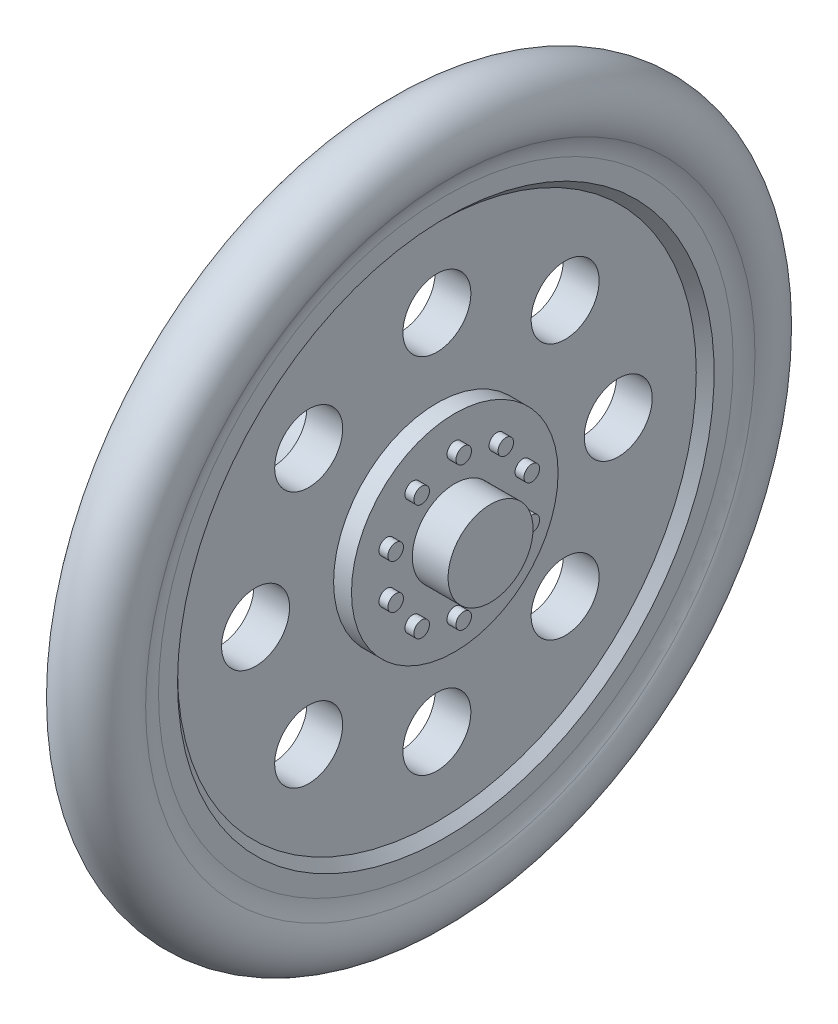
SolidWorks part; units mm, degrees
material "PE High Density"
ref_plane "Front Plane" through (0, 0, 0) normal (0, 0, 1) x (1, 0, 0)
ref_plane "Top Plane" through (0, 0, 0) normal (0, 1, 0) x (1, 0, 0)
ref_plane "Right Plane" through (0, 0, 0) normal (1, 0, 0) x (0, 0, -1)
sketch "Sketch1" plane through (0, 0, 0) normal (0, 0, 1) x (1, 0, 0)
  line L0 (0, 0) -> (17.1706, 0) construction
  line L1 (9.5, 0) -> (0, 0)
  line L2 (0, 0) -> (0, 3.1)
  line L3 (0, 3.1) -> (7.5, 3.1)
  line L4 (7.5, 3.1) -> (7.5, 14.5)
  line L5 (7.5, 7.7069) -> (9.5, 7.7069) construction
  line L6 (9.5, 14.5) -> (9.5, 0)
  line L7 (8.5, 7.7069) -> (8.5, 18) construction
  line L8 (10, 15) -> (9.5, 14.5)
  line L9 (7, 16.6771) -> (7, 15)
  line L10 (7, 15) -> (7.5, 14.5)
  line L11 (10, 16.6771) -> (10, 15)
  arc A0 (10, 16.6771) -> (7, 16.6771) centre (8.5, 18) ccw
  dimension "D1" = 4
  dimension "D3" = 40
  dimension "D5" = 6.5
  dimension "D2" = 2
  dimension "D4" = 6.2
  dimension "D6" = 29
  dimension "D7" = 0.5
  dimension "D8" = 45
revolve "Revolve1" add sketch "Sketch1" angle 360 about L0
fillet "Fillet1" radius 2 2 edges at (7, 0, 16.6771) (10, 0, 16.6771)
sketch "Sketch2" plane through (9.5, 0, 0) normal (1, 0, 0) x (0, 0, -1)
  circle A0 centre (0, 0) radius 5.775
  dimension "D1" = 11.55
extrude "Extrude1" add sketch "Sketch2" along normal blind 1
sketch "Sketch3" plane through (10.5, 0, 0) normal (1, 0, 0) x (0, 0, -1)
  circle A0 centre (0, 0) radius 2.375
  dimension "D1" = 4.75
extrude "Extrude2" add sketch "Sketch3" along normal blind 2
sketch "Sketch4" plane through (10.5, 0, 0) normal (1, 0, 0) x (0, 0, -1)
  circle A0 centre (0, 0) radius 4 construction
  circle A1 centre (0, 4) radius 0.435
  dimension "D1" = 0.87
  dimension "D2" = 8
extrude "Extrude3" add sketch "Sketch4" along normal blind 0.5
pattern_circular "CirPattern1" count 10 over 360 about axis through (0, 0, 0) along (1, 0, 0) of "Extrude3"
sketch "Sketch5" plane through (9.5, 0, 0) normal (1, 0, 0) x (0, 0, -1)
  circle A0 centre (0, 0) radius 10.1375 construction
  circle A1 centre (0, 10.1375) radius 1.9
  dimension "D1" = 3.8
  dimension "D2" = 20.275
extrude "Cut-Extrude1" cut sketch "Sketch5" against normal through all
pattern_circular "CirPattern2" count 8 over 360 about axis through (0, 0, 0) along (1, 0, 0) of "Cut-Extrude1"
sketch "Sketch6" plane through (0, 0, 0) normal (-1, 0, 0) x (0, 0, 1)
  circle A0 centre (0, 0) radius 1.63
  dimension "D1" = 3.26
extrude "Cut-Extrude2" cut sketch "Sketch6" against normal offset from surface (10.9125 mm away) 1.5875 up to face at (12.5, 0, -2.375)
